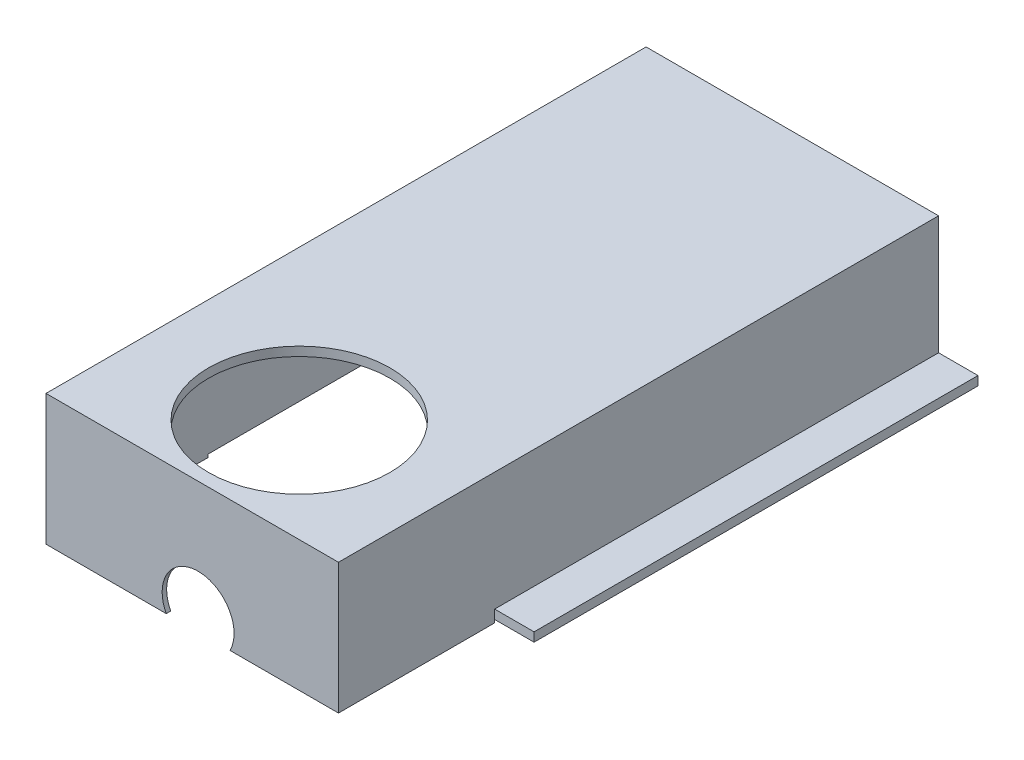
SolidWorks part; units mm, degrees
ref_plane "Front Plane" through (0, 0, 0) normal (0, 0, 1) x (1, 0, 0)
ref_plane "Top Plane" through (0, 0, 0) normal (0, 1, 0) x (1, 0, 0)
ref_plane "Right Plane" through (0, 0, 0) normal (1, 0, 0) x (0, 0, -1)
sketch "Sketch1" plane through (0, 0, 0) normal (0, 1, 0) x (1, 0, 0)
  line L1 (0, 0) -> (97.58, 0)
  line L2 (0, 0) -> (0, 200.21)
  line L3 (0, 200.21) -> (97.58, 200.21)
  line L4 (97.58, 0) -> (97.58, 200.21)
  dimension "D1" = 97.58
  dimension "D2" = 200.21
extrude "Boss-Extrude1" add sketch "Sketch1" along normal blind 43.58
sketch "Sketch2" plane through (0, 0, 0) normal (0, -1, 0) x (1, 0, 0)
  line L1 (0, -200.21) -> (2, -200.21)
  line L2 (0, -200.21) -> (0, -52.1)
  line L3 (0, -52.1) -> (2, -52.1)
  line L4 (2, -200.21) -> (2, -52.1)
  dimension "D1" = 148.11
  dimension "D2" = 2
extrude "Cut-Extrude1" cut sketch "Sketch2" against normal blind 1
sketch "Sketch3" plane through (2, 0, 0) normal (-1, 0, 0) x (0, 0, 1)
  line L1 (-200.21, 0) -> (-52.1, 0)
  line L2 (-200.21, 0) -> (-200.21, 1)
  line L3 (-200.21, 1) -> (-52.1, 1)
  line L4 (-52.1, 0) -> (-52.1, 1)
extrude "Cut-Extrude2" cut sketch "Sketch3" against normal blind 100
sketch "Sketch4" plane through (0, 0, 0) normal (0, -1, 0) x (-1, 0, 0)
  line L0 (0, 0) -> (-2, 0) construction
  line L1 (0, 0) -> (-97.58, 0) construction
  line L2 (-2, 0) -> (-2, 1.5) construction
  line L3 (-97.58, 52.1) -> (-95.58, 52.1) construction
  line L4 (-97.58, 52.1) -> (0, 52.1) construction
  line L6 (-2, 1.5) -> (-95.58, 1.5)
  line L7 (-2, 1.5) -> (-2, 52.1)
  line L8 (-2, 52.1) -> (-95.58, 52.1)
  line L9 (-95.58, 1.5) -> (-95.58, 52.1)
extrude "Cut-Extrude4" cut sketch "Sketch4" against normal blind 40.58
sketch "Sketch5" plane through (0, 1, 0) normal (0, -1, 0) x (-1, 0, 0)
  line L0 (-97.58, 200.21) -> (-95.58, 200.21) construction
  line L1 (0, 200.21) -> (-97.58, 200.21) construction
  line L2 (-95.58, 52.1) -> (-2, 52.1) construction
  line L3 (-95.58, 200.21) -> (-2, 200.21)
  line L4 (-95.58, 200.21) -> (-95.58, 52.1)
  line L5 (-95.58, 52.1) -> (-2, 52.1)
  line L6 (-2, 200.21) -> (-2, 52.1)
extrude "Cut-Extrude5" cut sketch "Sketch5" against normal blind 39.58
sketch "Sketch6" plane through (0, 0, 0) normal (0, 0, 1) x (1, 0, 0)
  line L0 (98.3468, 0) -> (50.7468, 0) construction
  line L1 (0, 0) -> (97.58, 0) construction
  line L2 (50.7468, 0) -> (50.7468, 5.57) construction
  circle A0 centre (50.7468, 5.57) radius 12
  point P6 (0, 0)
extrude "Cut-Extrude6" cut sketch "Sketch6" against normal blind 39.58
sketch "Sketch7" plane through (0, 43.58, 0) normal (0, 1, 0) x (1, 0, 0)
  line L0 (97.58, 0) -> (49.98, 0) construction
  line L1 (0, 0) -> (97.58, 0) construction
  line L2 (49.98, 0) -> (49.98, 34.51) construction
  circle A0 centre (49.98, 34.51) radius 30.26
  dimension "D1" = 60.52
extrude "Cut-Extrude7" cut sketch "Sketch7" against normal blind 39.58
sketch "Sketch10" plane through (0, 0, 0) normal (-1, 0, 0) x (0, 0, 1)
  line L0 (-200.21, 1) -> (-200.21, 4)
  line L1 (-200.21, 43.58) -> (-200.21, 1) construction
  line L2 (-200.21, 1) -> (-52.1, 1)
  line L3 (-52.1, 1) -> (-52.1, 4)
  line L4 (-52.1, 4) -> (-200.21, 4)
extrude "Boss-Extrude2" add sketch "Sketch10" along normal blind 13.15
sketch "Sketch11" plane through (97.58, 0, 0) normal (1, 0, 0) x (0, 0, -1)
  line L0 (200.21, 1) -> (200.21, 4)
  line L1 (200.21, 43.58) -> (200.21, 1) construction
  line L2 (200.21, 1) -> (52.1, 1)
  line L3 (52.1, 1) -> (52.1, 4)
  line L4 (52.1, 4) -> (200.21, 4)
extrude "Boss-Extrude3" add sketch "Sketch11" along normal blind 13.15
